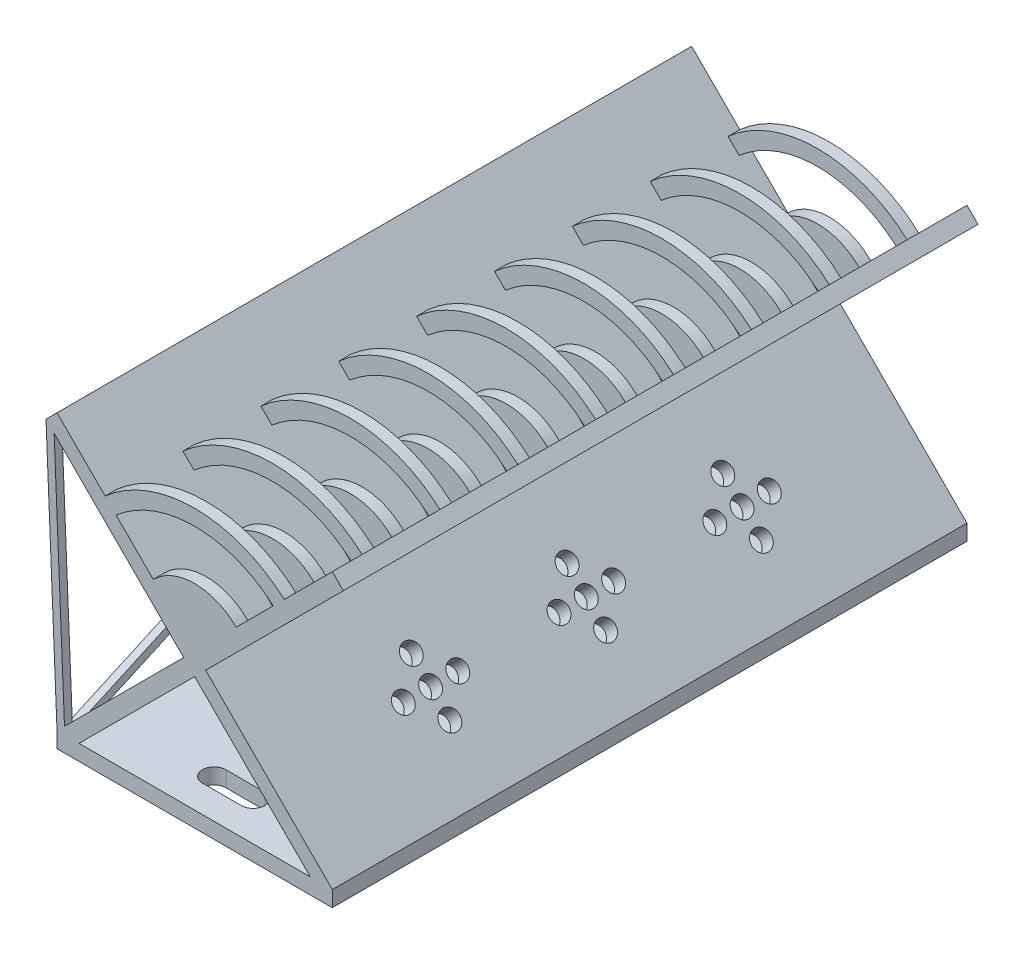
SolidWorks part; units mm, degrees
ref_plane "Front Plane" through (0, 0, 0) normal (0, 0, 1) x (1, 0, 0)
ref_plane "Top Plane" through (0, 0, 0) normal (0, 1, 0) x (1, 0, 0)
ref_plane "Right Plane" through (0, 0, 0) normal (1, 0, 0) x (0, 0, -1)
sketch "Sketch1" plane through (0, 0, 0) normal (0, 0, 1) x (1, 0, 0)
  line L2 (-44.9013, 44.9013) -> (44.9013, -44.9013)
  line L3 (-44.9013, -44.9013) -> (44.9013, 44.9013)
  line L4 (70.1358, 0) -> (-70.1358, 0) construction
  point P0 (0, 0)
  point P8 (0, 0)
  dimension "D1" = 90
  dimension "D2" = 127
  dimension "D3" = 127
  dimension "D4" = 45
extrude "Frame" add sketch "Sketch1" along normal blind 207.01 thin
sketch "Sketch12" plane through (0, 0, 0) normal (0, 0, 1) x (1, 0, 0)
  line L0 (-44.9013, -44.9013) -> (44.9013, -44.9013)
  line L1 (-44.9013, -44.9013) -> (-44.9013, -50.0143)
  line L2 (44.9013, -44.9013) -> (44.9013, -50.0143)
  line L3 (-44.9013, -50.0143) -> (44.9013, -50.0143)
extrude "Bottom Platform" add sketch "Sketch12" along normal up to surface (207.01 mm away) up to face at (1.7961, -1.7961, 207.01)
sketch "Sketch13" plane through (0, -50.0143, 0) normal (0, -1, 0) x (-1, 0, 0)
  line L0 (-44.9013, -207.01) -> (44.9013, -207.01) construction
  line L1 (44.9013, -207.01) -> (44.9013, 0) construction
  circle A0 centre (32.2013, -194.31) radius 3.81
  dimension "D1" = 7.62
  dimension "D3" = 12.7
  dimension "D2" = 12.7
extrude "Rubber Pads 1" add sketch "Sketch13" along normal blind 3.81 draft 10
mirror "Rubber Pads 1 Mirror" about plane through (0, 0, 0) normal (1, 0, 0) of "Rubber Pads 1"
sketch "Sketch15" plane through (0, -50.0143, 0) normal (0, -1, 0) x (1, 0, 0)
  line L0 (55, 0) -> (-55, 0) construction
  line L1 (44.9013, 207.01) -> (44.9013, 0) construction
  circle A0 centre (32.2013, 12.7) radius 3.81
  dimension "D1" = 7.62
  dimension "D2" = 12.7
  dimension "D3" = 12.7
extrude "Rubber Pads 2" add sketch "Sketch15" along normal blind 3.81 draft 10
mirror "Rubber Pads 2 Mirror" about plane through (0, 0, 0) normal (1, 0, 0) of "Rubber Pads 2"
sketch "Sketch21" plane through (0, -50.0143, 0) normal (0, -1, 0) x (1, 0, 0)
  line L0 (6.35, 12.7) -> (-6.35, 12.7) construction
  line L1 (0, -54.2991) -> (0, 54.2991) construction
  line L2 (6.35, 8.89) -> (-6.35, 8.89)
  line L3 (6.35, 16.51) -> (-6.35, 16.51)
  line L4 (53.3427, 0) -> (-53.3427, 0) construction
  line L5 (6.35, 194.31) -> (-6.35, 194.31) construction
  line L6 (44.9013, 207.01) -> (-44.9013, 207.01) construction
  line L7 (6.35, 190.5) -> (-6.35, 190.5)
  line L8 (6.35, 198.12) -> (-6.35, 198.12)
  arc A0 (6.35, 8.89) -> (6.35, 16.51) centre (6.35, 12.7) ccw
  arc A1 (-6.35, 16.51) -> (-6.35, 8.89) centre (-6.35, 12.7) ccw
  arc A2 (6.35, 190.5) -> (6.35, 198.12) centre (6.35, 194.31) ccw
  arc A3 (-6.35, 198.12) -> (-6.35, 190.5) centre (-6.35, 194.31) ccw
  point P4 (0, 12.7)
  point P15 (0, 194.31)
  dimension "D1" = 12.7
  dimension "D2" = 12.7
extrude "Cable Holes" cut sketch "Sketch21" against normal up to next
sketch "Sketch23" plane through (0, 0, 207.01) normal (0, 0, 1) x (1, 0, 0)
  line L0 (0, 0) -> (44.9013, 44.9013) construction
  line L1 (-44.9013, 44.9013) -> (0, 0) construction
  line L13 (44.9013, 44.9013) -> (0, 0)
  line L14 (0, 0) -> (-44.9013, 44.9013)
  line L15 (-44.9013, 44.9013) -> (-48.4934, 41.3092)
  line L16 (-48.4934, 41.3092) -> (-3.5921, -3.5921)
  line L17 (-3.5921, -3.5921) -> (-44.9013, -44.9013)
  line L18 (-44.9013, -44.9013) -> (-44.9013, -50.0143)
  line L19 (-44.9013, -50.0143) -> (44.9013, -50.0143)
  line L20 (44.9013, -50.0143) -> (44.9013, -44.9013)
  line L21 (44.9013, -44.9013) -> (3.5921, -3.5921)
  line L22 (3.5921, -3.5921) -> (48.4934, 41.3092)
  line L23 (48.4934, 41.3092) -> (44.9013, 44.9013)
  line L24 (13.5162, 13.5162) -> (0, 0)
  line L25 (0, 0) -> (-13.5162, 13.5162)
  arc A0 (13.5162, 13.5162) -> (-13.5162, 13.5162) centre (0, 0) ccw
  dimension "D1" = 0
extrude "Bottom Separators" add sketch "Sketch23" against normal blind 3.81
pattern_linear "Bottom Separators Pattern" count 9 spacing 25.4 along (0, 0, -1) of "Bottom Separators"
sketch "Sketch25" plane through (0, 0, 207.01) normal (0, 0, 1) x (1, 0, 0)
  line L0 (-44.9013, 44.9013) -> (-13.5162, 13.5162) construction
  line L1 (13.5162, 13.5162) -> (44.9013, 44.9013) construction
  line L2 (-29.2087, 29.2087) -> (-25.6166, 25.6166)
  line L3 (29.2087, 29.2087) -> (25.6166, 25.6166)
  arc A0 (-29.2087, 29.2087) -> (29.2087, 29.2087) centre (0, -3.462) cw
  arc A1 (-25.6166, 25.6166) -> (25.6166, 25.6166) centre (0, -3.498) cw
  point P10 (0, 40.3618)
  point P11 (0, 35.2818)
  dimension "D1" = 5.08
  dimension "D2" = 5.08
  dimension "D3" = 5.08
extrude "Top Separators" add sketch "Sketch25" against normal blind 3.81
pattern_linear "Top Separators Pattern" count 9 spacing 25.4 along (0, 0, -1) of "Top Separators"
sketch "Sketch27" plane through (0, 0, 0) normal (0.7071, 0.7071, 0) x (0, 0, -1)
  line L0 (-207.01, -5.08) -> (-207.01, -63.5) construction
  line L1 (-207.01, -63.5) -> (0, -63.5) construction
  circle A1 centre (-112.395, -34.29) radius 3.175
  circle A2 centre (-103.505, -34.29) radius 3.175
  circle A3 centre (-94.615, -34.29) radius 3.175
  circle A4 centre (-103.505, -25.4) radius 3.175
  circle A5 centre (-103.505, -43.18) radius 3.175
  point P0 (-207.01, -34.29)
  point P21 (-103.505, -63.5)
  dimension "D1" = 6.35
  dimension "D3" = 8.89
  dimension "D4" = 8.89
  dimension "D5" = 8.89
  dimension "D6" = 8.89
extrude "Speaker Holes" cut sketch "Sketch27" against normal up to next
pattern_linear "Speaker Holes Pattern 1" count 2 spacing 50.8 along (0, 0, 1) of "Speaker Holes"
pattern_linear "Speaker Holes Pattern 2" count 2 spacing 50.8 along (0, 0, -1) of "Speaker Holes"
mirror "Speaker Holes Mirror" about plane through (0, 0, 0) normal (1, 0, 0) of "Speaker Holes Pattern 2", "Speaker Holes Pattern 1", "Speaker Holes"
sketch "Sketch38" plane through (0, 0, 0) normal (0, 0, -1) x (-1, 0, 0)
  line L0 (48.4934, 41.3092) -> (44.9013, -44.9013)
extrude "Extrude-Thin2" add sketch "Sketch38" against normal blind 2.54 thin
sketch "Sketch40" plane through (0, 0, 207.01) normal (0, 0, 1) x (1, 0, 0)
  line L0 (-48.4934, 41.3092) -> (-44.9013, -44.9013)
extrude "Extrude-Thin5" add sketch "Sketch40" against normal blind 2.54 thin thin type one direction reverse wall 2.54
sketch "Sketch48" plane through (-46.6911, -1.9455, 0) normal (-0.9991, -0.0416, 0) x (0, 0, 1)
  line L0 (2.54, 43.2922) -> (204.47, -42.9931)
  line L1 (2.54, -42.9931) -> (204.47, 43.2922)
extrude "Extrude-Thin9" add sketch "Sketch48" against normal blind 2.54 thin
